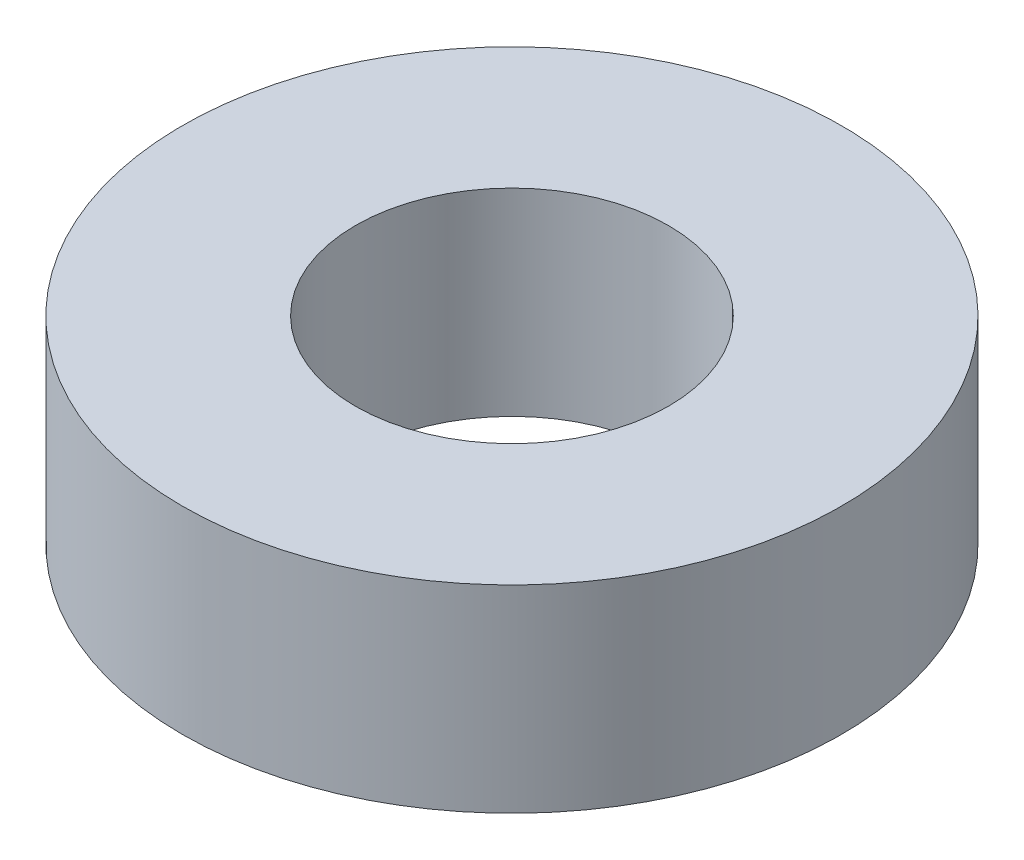
SolidWorks part; units mm, degrees
ref_plane "前视基准面" through (0, 0, 0) normal (0, 0, 1) x (1, 0, 0)
ref_plane "上视基准面" through (0, 0, 0) normal (0, 1, 0) x (1, 0, 0)
ref_plane "右视基准面" through (0, 0, 0) normal (1, 0, 0) x (0, 0, -1)
other "Configuration Table"
sketch "草图1" plane through (0, 0, 0) normal (0, 1, 0) x (1, 0, 0)
  circle A0 centre (0, 0) radius 5
  circle A1 centre (0, 0) radius 2.375
  dimension "D1" = 4.75
  dimension "D2" = 10
extrude "凸台-拉伸1" add sketch "草图1" along normal blind 3
